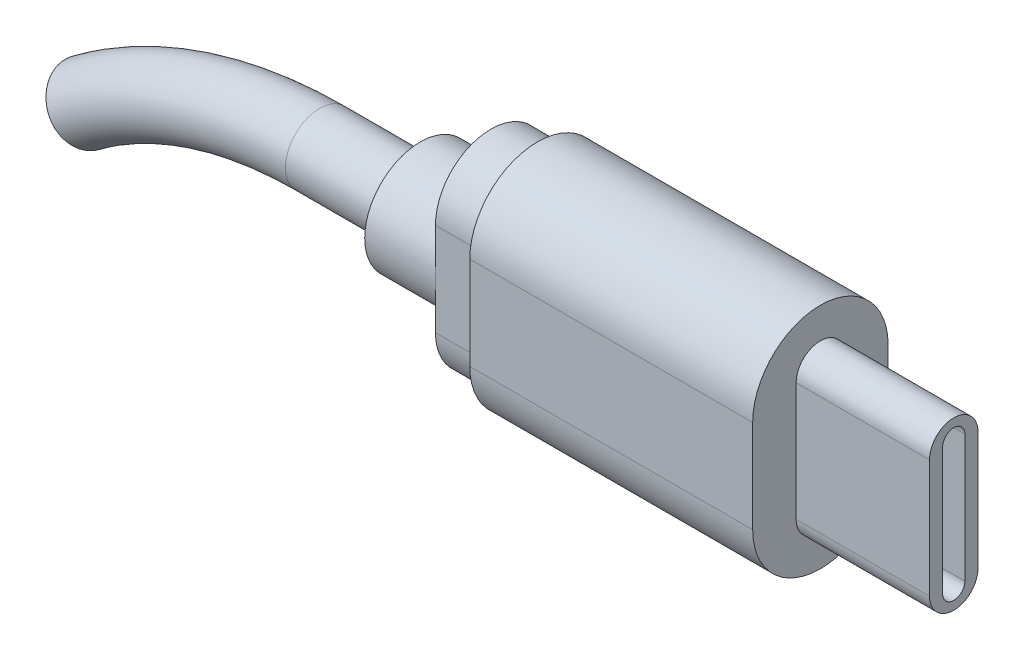
SolidWorks part; units mm, degrees
ref_plane "Front" through (0, 0, 0) normal (0, 0, 1) x (1, 0, 0)
ref_plane "Top" through (0, 0, 0) normal (0, 1, 0) x (1, 0, 0)
ref_plane "Right" through (0, 0, 0) normal (1, 0, 0) x (0, 0, -1)
sketch "Эскиз1" plane through (0, 0, 0) normal (1, 0, 0) x (0, 0, -1)
  line L0 (0, -2.3) -> (0, 2.3) construction
  line L1 (-3.35, -2.3) -> (-3.35, 2.3)
  line L2 (3.35, -2.3) -> (3.35, 2.3)
  arc A0 (-3.35, -2.3) -> (3.35, -2.3) centre (0, -2.3) ccw
  arc A1 (3.35, 2.3) -> (-3.35, 2.3) centre (0, 2.3) ccw
  point P2 (0, 0)
  point P8 (0, -5.65)
  point P9 (0, 5.65)
  dimension "D1" = 6.7
  dimension "D2" = 11.3
extrude "Бобышка-Вытянуть1" add sketch "Эскиз1" against normal blind 14
sketch "Эскиз3" plane through (-14, 0, 0) normal (-1, 0, 0) x (0, 0, 1)
  line L0 (0, 2.3) -> (0, -2.3) construction
  line L1 (2.75, 2.3) -> (2.75, -2.3)
  line L2 (-2.75, 2.3) -> (-2.75, -2.3)
  arc A0 (2.75, 2.3) -> (-2.75, 2.3) centre (0, 2.3) ccw
  arc A1 (-2.75, -2.3) -> (2.75, -2.3) centre (0, -2.3) ccw
  arc A2 (-3.35, -2.3) -> (3.35, -2.3) centre (0, -2.3) ccw construction
  point P2 (0, 0)
  dimension "D1" = 5.5
extrude "Бобышка-Вытянуть2" add sketch "Эскиз3" along normal offset from surface (2.3 mm away) 16.3 up to face at (0, 0, 0)
sketch "Эскиз4" plane through (-16.3, 0, 0) normal (-1, 0, 0) x (0, 0, 1)
  line L0 (-2.75, -2.3) -> (-2.75, 2.3) construction
  circle A0 centre (0, 0) radius 2.75
extrude "Бобышка-Вытянуть3" add sketch "Эскиз4" along normal blind 3.5
sketch "Эскиз5" plane through (-19.8, 0, 0) normal (-1, 0, 0) x (0, 0, 1)
  circle A0 centre (0, 0) radius 1.7
  dimension "D1" = 3.4
sketch "Эскиз6" plane through (0, 0, 0) normal (0, 0, 1) x (1, 0, 0)
  line L0 (-19.8, 0) -> (-24.7762, 0)
  line L1 (-19.8, 1.7) -> (-19.8, -1.7) construction
  arc A0 (-24.7762, 0) -> (-36.3422, -3.8456) centre (-24.7762, -19.3158) ccw
sweep "По траектории1" add profiles "Эскиз5" path "Эскиз6"
sketch "Эскиз7" plane through (0, 0, 0) normal (1, 0, 0) x (0, 0, -1)
  line L5 (0, -2.925) -> (0, 2.925) construction
  line L6 (-1.2, -2.925) -> (-1.2, 2.925)
  line L8 (1.2, -2.925) -> (1.2, 2.925)
  line L9 (0, -3.15) -> (0, 3.15) construction
  line L10 (-0.55, -3.15) -> (-0.55, 3.15)
  line L11 (0.55, -3.15) -> (0.55, 3.15)
  arc A0 (-1.2, -2.925) -> (1.2, -2.925) centre (0, -2.925) ccw
  arc A1 (1.2, 2.925) -> (-1.2, 2.925) centre (0, 2.925) ccw
  arc A2 (-0.55, -3.15) -> (0.55, -3.15) centre (0, -3.15) ccw
  arc A3 (0.55, 3.15) -> (-0.55, 3.15) centre (0, 3.15) ccw
  point P2 (0, 0)
  point P7 (0, 4.125)
  point P8 (0, -4.125)
  point P11 (0, 0)
  point P18 (0.5, 3.1691)
  dimension "D3" = 0.55
  dimension "D1" = 8.25
  dimension "D2" = 2.4
  dimension "D4" = 6.3
extrude "Бобышка-Вытянуть4" add sketch "Эскиз7" along normal blind 6.6
